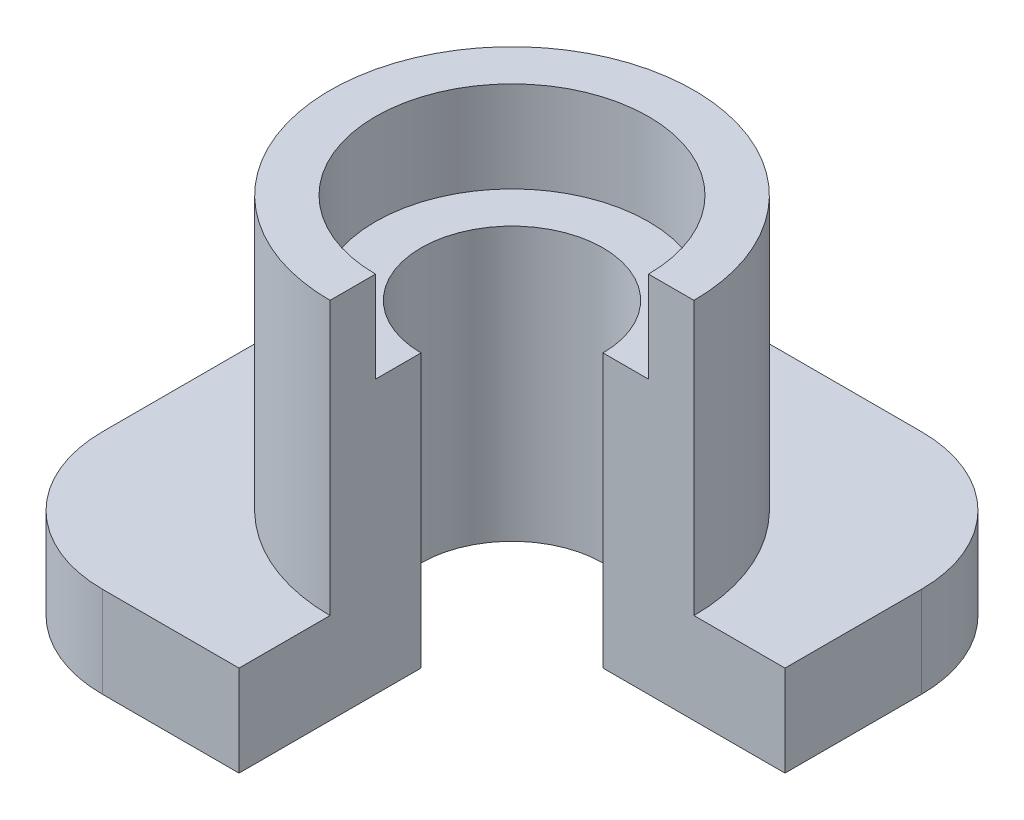
SolidWorks part; units mm, degrees
ref_plane "Alzado" through (0, 0, 0) normal (0, 0, 1) x (1, 0, 0)
ref_plane "Planta" through (0, 0, 0) normal (0, 1, 0) x (1, 0, 0)
ref_plane "Vista lateral" through (0, 0, 0) normal (1, 0, 0) x (0, 0, -1)
sketch "Croquis1" plane through (0, 0, 0) normal (0, 1, 0) x (1, 0, 0)
  line L1 (-30, 60) -> (30, 60)
  line L2 (-60, 30) -> (-60, -30)
  line L3 (-30, -60) -> (30, -60)
  line L4 (60, 30) -> (60, -30)
  line L5 (-60, 60) -> (60, -60) construction
  line L6 (-60, -60) -> (60, 60) construction
  arc A0 (30, 60) -> (60, 30) centre (30, 30) cw
  arc A1 (60, -30) -> (30, -60) centre (30, -30) cw
  arc A2 (-30, -60) -> (-60, -30) centre (-30, -30) cw
  arc A3 (-30, 60) -> (-60, 30) centre (-30, 30) ccw
  point P0 (0, 0)
  dimension "D3" = 30
  dimension "D1" = 120
  dimension "D2" = 120
extrude "Saliente-Extruir1" add sketch "Croquis1" along normal blind 20
sketch "Croquis2" plane through (0, 20, 0) normal (0, 1, 0) x (1, 0, 0)
  circle A0 centre (0, 0) radius 40
extrude "Saliente-Extruir2" add sketch "Croquis2" along normal blind 60
sketch "Croquis3" plane through (0, 80, 0) normal (0, 1, 0) x (1, 0, 0)
  circle A0 centre (0, 0) radius 30
extrude "Cortar-Extruir1" cut sketch "Croquis3" against normal blind 20
sketch "Croquis4" plane through (0, 60, 0) normal (0, 1, 0) x (1, 0, 0)
  circle A0 centre (0, 0) radius 20
extrude "Cortar-Extruir2" cut sketch "Croquis4" against normal through all
sketch "Croquis6" plane through (0, 80, 0) normal (0, 1, 0) x (1, 0, 0)
  line L1 (0, 0) -> (71.7041, 0)
  line L2 (0, 0) -> (0, -65.2069)
  line L3 (0, -65.2069) -> (71.7041, -65.2069)
  line L4 (71.7041, 0) -> (71.7041, -65.2069)
extrude "Cortar-Extruir4" cut sketch "Croquis6" against normal through all
